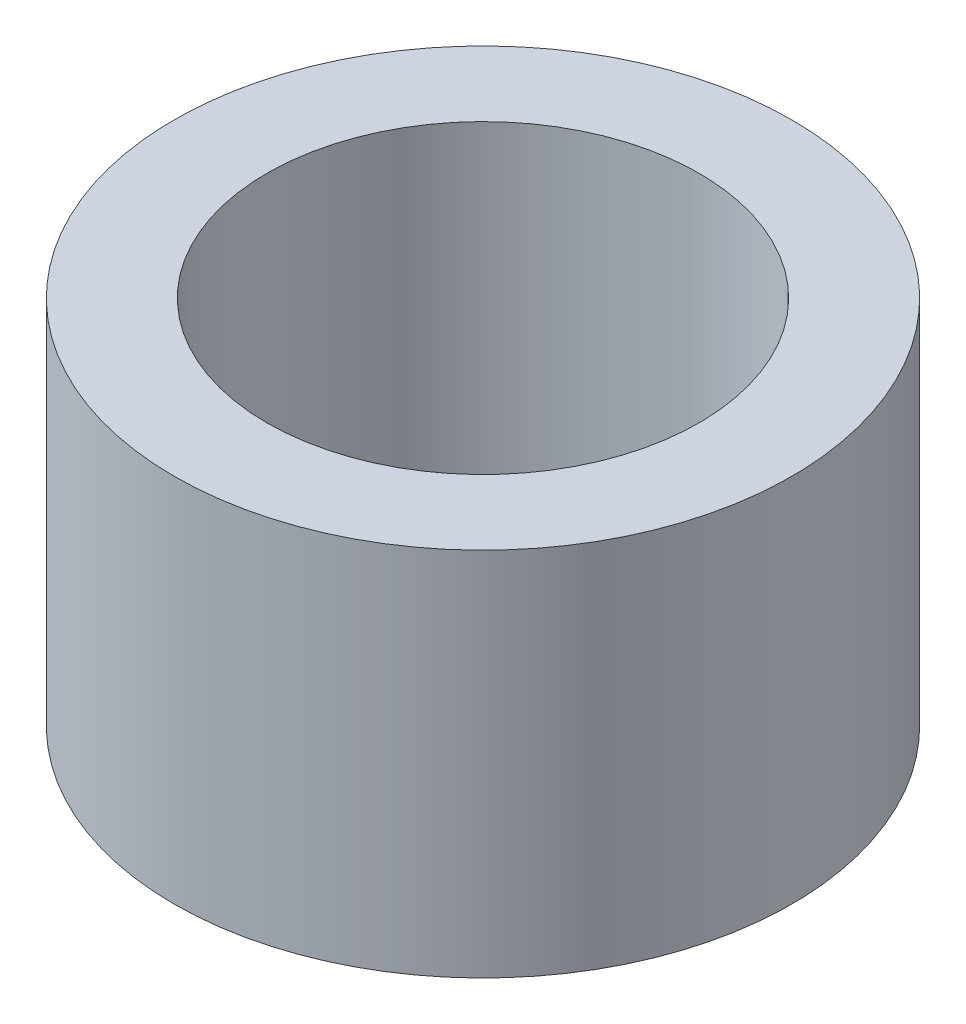
SolidWorks part; units mm, degrees
material "Nylon 101"
ref_plane "Front Plane" through (0, 0, 0) normal (0, 0, 1) x (1, 0, 0)
ref_plane "Top Plane" through (0, 0, 0) normal (0, 1, 0) x (1, 0, 0)
ref_plane "Right Plane" through (0, 0, 0) normal (1, 0, 0) x (0, 0, -1)
sketch "Sketch1" plane through (0, 0, 0) normal (0, 1, 0) x (1, 0, 0)
  circle A0 centre (0, 0) radius 2.5
  circle A1 centre (0, 0) radius 1.75
  dimension "D1" = 5
  dimension "D2" = 3.5
extrude "Boss-Extrude1" add sketch "Sketch1" along normal blind 3
